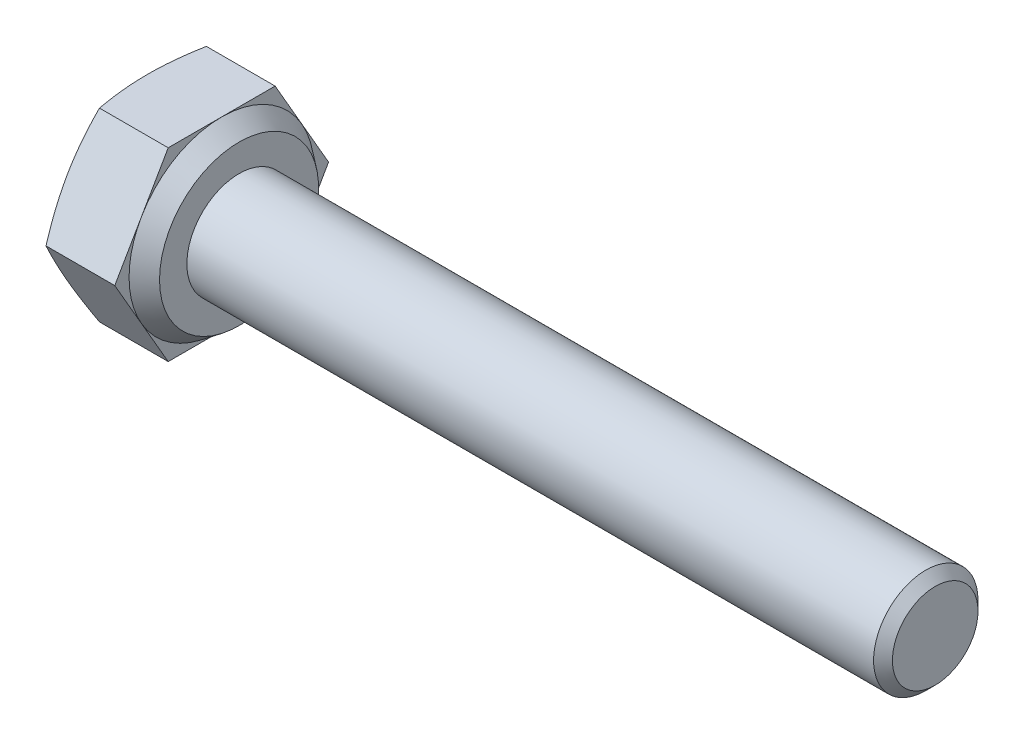
SolidWorks part; units mm, degrees
ref_plane "Front" through (0, 0, 0) normal (0, 0, 1) x (1, 0, 0)
ref_plane "Top" through (0, 0, 0) normal (0, 1, 0) x (1, 0, 0)
ref_plane "Right" through (0, 0, 0) normal (1, 0, 0) x (0, 0, -1)
other "Configuration Table"
sketch "Sketch-BaseHead" plane through (0, 0, 0) normal (1, 0, 0) x (0, 0, -1)
  line L1 (3.0715, 0) -> (1.5358, 2.66)
  line L2 (1.5358, 2.66) -> (-1.5358, 2.66)
  line L3 (-1.5358, 2.66) -> (-3.0715, 0)
  line L4 (-3.0715, 0) -> (-1.5358, -2.66)
  line L5 (-1.5358, -2.66) -> (1.5358, -2.66)
  line L6 (1.5358, -2.66) -> (3.0715, 0)
  circle A0 centre (0, 0) radius 2.66 construction
extrude "BaseHead" add sketch "Sketch-BaseHead" along normal blind 2.125
sketch "Sketch4" plane through (-0.2646, 0, 5.9169) normal (0, 1, 0) x (0, 0, -1)
  line L0 (5.9169, 3.7369) -> (5.9169, -10.4477) construction
  line L2 (8.9884, -0.2646) -> (8.5769, -0.2646)
  line L4 (8.5769, -0.2646) -> (8.9884, -0.4144)
  line L6 (8.9884, -0.4144) -> (8.9884, -0.2646)
  dimension "D1" = 20
revolve "HeadChamfer" cut sketch "Sketch4" angle 360 about L0
sketch "Sketch1" plane through (0, 0, 0) normal (0, 0, 1) x (1, 0, 0)
  line L0 (2.125, 0) -> (2.625, 0)
  line L1 (2.625, 0) -> (2.625, -2.285)
  line L2 (2.625, -2.285) -> (2.125, -2.66)
  line L3 (2.125, -2.66) -> (2.125, 0) construction
  line L4 (0, 0) -> (7.5821, 0) construction
  line L5 (-4.0016, 0) -> (10.1831, 0) construction
  line L6 (2.125, -2.66) -> (0.1498, -2.66) construction
  line L7 (2.125, 0) -> (2.125, -2.66)
  dimension "c" = 0.5
revolve "Revolve1" add sketch "Sketch1" angle 360 about axis through (-4.0016, 0, 0) along (1, 0, 0)
ref_plane "Plane2" through (10.625, 0, 0) normal (1, 0, 0) x (0, 0, -1)
sketch "Sketch3" plane through (2.625, 0, 0) normal (1, 0, 0) x (0, 0, -1)
  circle A0 centre (0, 0) radius 1.5
extrude "BaseBody" add sketch "Sketch3" along normal blind 20
cosmetic thread "ThreadCosmetic1" [suppressed] parameters "b"=12, "D2"=2.459
fillet "HeadFillet" [suppressed] radius 0.1
chamfer "Chamfer1" distance 0.2705 angle 45 1 edges at (22.625, 0, -1.5)
sketch "Sketch5" plane through (0, 0, 0) normal (0, 0, 1) x (1, 0, 0)
  line L0 (22.084, 1.7705) -> (22.3545, 1.7705)
  line L1 (22.3545, 1.7705) -> (22.3545, 1.5)
  line L2 (22.3545, 1.5) -> (22.2192, 1.2657)
  line L3 (22.2192, 1.2657) -> (22.084, 1.5)
  line L4 (22.084, 1.5) -> (22.084, 1.7705)
  line L5 (22.3545, -1.5) -> (22.3545, 1.5) construction
  line L6 (22.3545, 1.5) -> (2.625, 1.5) construction
revolve "Cut-Revolve10" [suppressed] cut sketch "Sketch5" angle 360
pattern_linear "LPattern10" [suppressed] count 37
equation "\"D1@Sketch1\" = \"s@Sketch-BaseHead\"/ 2"
equation "\"D2@Sketch4\" = \"s@Sketch-BaseHead\""
equation "\"D1@Chamfer1\" =  ( \"d@Sketch3\" - \"D2@ThreadCosmetic1\" ) / 2 "
equation "\"b@ThreadCosmetic1\" = \"l@BaseBody\" - \"lg@Plane2\""
equation "\"D1@Sketch5\" =  (\"d@Sketch3\" - \"D2@ThreadCosmetic1\" )  / 2 "
equation "\"pitch@LPattern10\" = 1.2 * \"D1@Sketch5\""
equation "\"D1@LPattern10\" = \"b@ThreadCosmetic1\" / \"pitch@LPattern10\""
